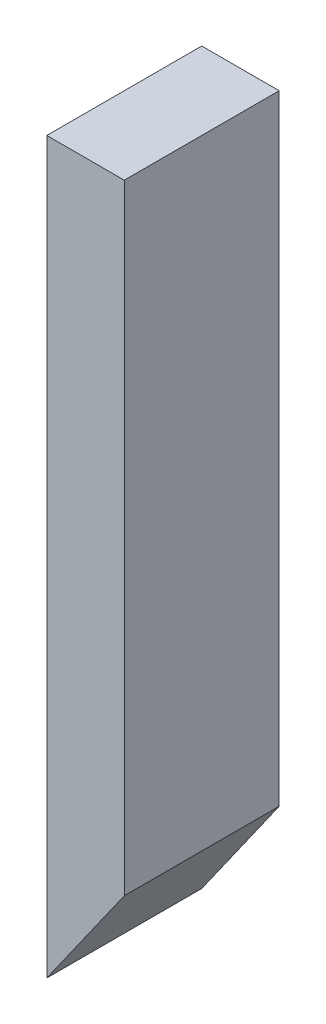
SolidWorks part; units mm, degrees
ref_plane "Front Plane" through (0, 0, 0) normal (0, 0, 1) x (1, 0, 0)
ref_plane "Top Plane" through (0, 0, 0) normal (0, 1, 0) x (1, 0, 0)
ref_plane "Right Plane" through (0, 0, 0) normal (1, 0, 0) x (0, 0, -1)
sketch "Sketch1" plane through (0, 0, 0) normal (0, 0, 1) x (1, 0, 0)
  line L0 (-11.9444, -26.3889) -> (-11.9444, -33.4849)
  line L1 (-11.9444, 13.6111) -> (-6.9444, 13.6111)
  line L2 (-11.9444, 13.6111) -> (-11.9444, -26.3889)
  line L4 (-6.9444, 13.6111) -> (-6.9444, -26.3889)
  line L5 (-11.9444, -33.4849) -> (-6.9444, -26.3889)
  dimension "D1" = 5
  dimension "D2" = 40
extrude "Boss-Extrude1" add sketch "Sketch1" along normal blind 10
